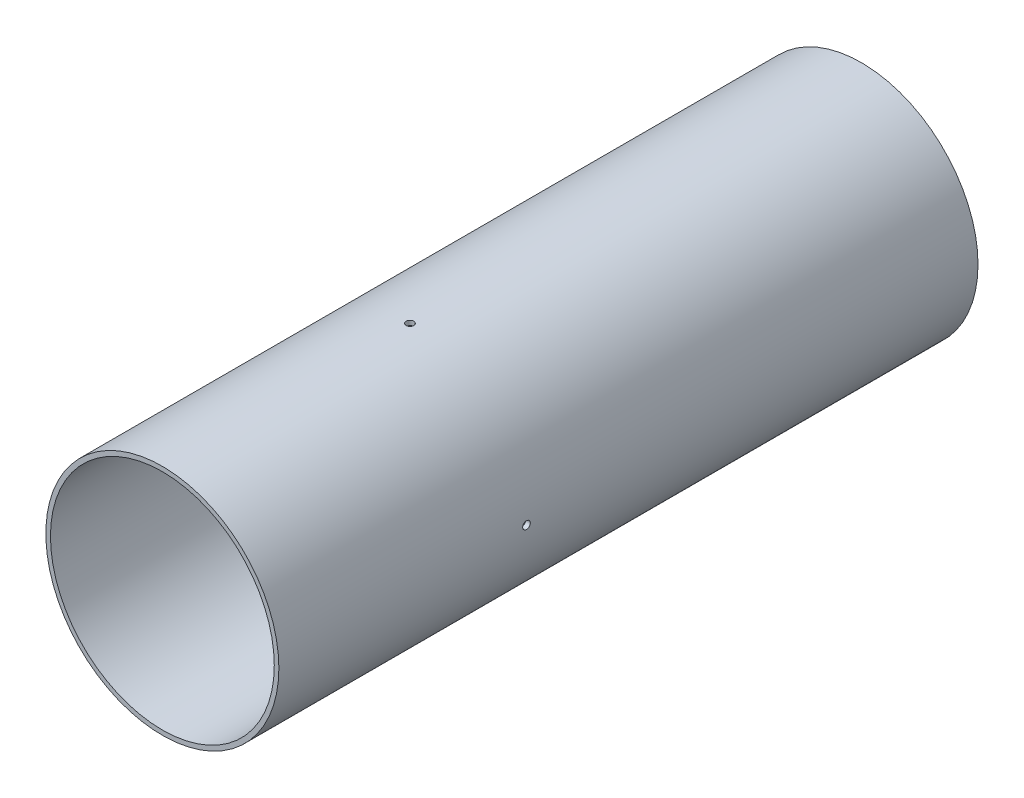
SolidWorks part; units mm, degrees
ref_plane "Front Plane" through (0, 0, 0) normal (0, 0, 1) x (1, 0, 0)
ref_plane "Top Plane" through (0, 0, 0) normal (0, 1, 0) x (1, 0, 0)
ref_plane "Right Plane" through (0, 0, 0) normal (1, 0, 0) x (0, 0, -1)
sketch "Sketch1" plane through (0, 0, 0) normal (0, 0, 1) x (1, 0, 0)
  circle A0 centre (0, 0) radius 50.8
  circle A1 centre (0, 0) radius 48.7934
  dimension "D1" = 101.6
  dimension "D2" = 2.0066
extrude "Boss-Extrude1" add sketch "Sketch1" along normal blind 304.8
ref_plane "Plane1" through (-50.8, 0, 0) normal (-1, 0, 0) x (0, 0, 1)
sketch "Sketch2" plane through (-50.8, 0, 0) normal (-1, 0, 0) x (0, 0, 1)
  line L0 (304.8, 0) -> (0, 0) construction
  line L1 (304.8, -50.8) -> (304.8, 50.8) construction
  line L2 (0, 50.8) -> (0, -50.8) construction
  circle A0 centre (196.85, 0) radius 1.651
  dimension "D1" = 107.95
  dimension "D2" = 3.302
extrude "Cut-Extrude1" cut sketch "Sketch2" against normal up to next
pattern_circular "CirPattern1" count 4 over 360 about axis through (0, 0, 304.8) along (0, 0, -1) of "Cut-Extrude1"
